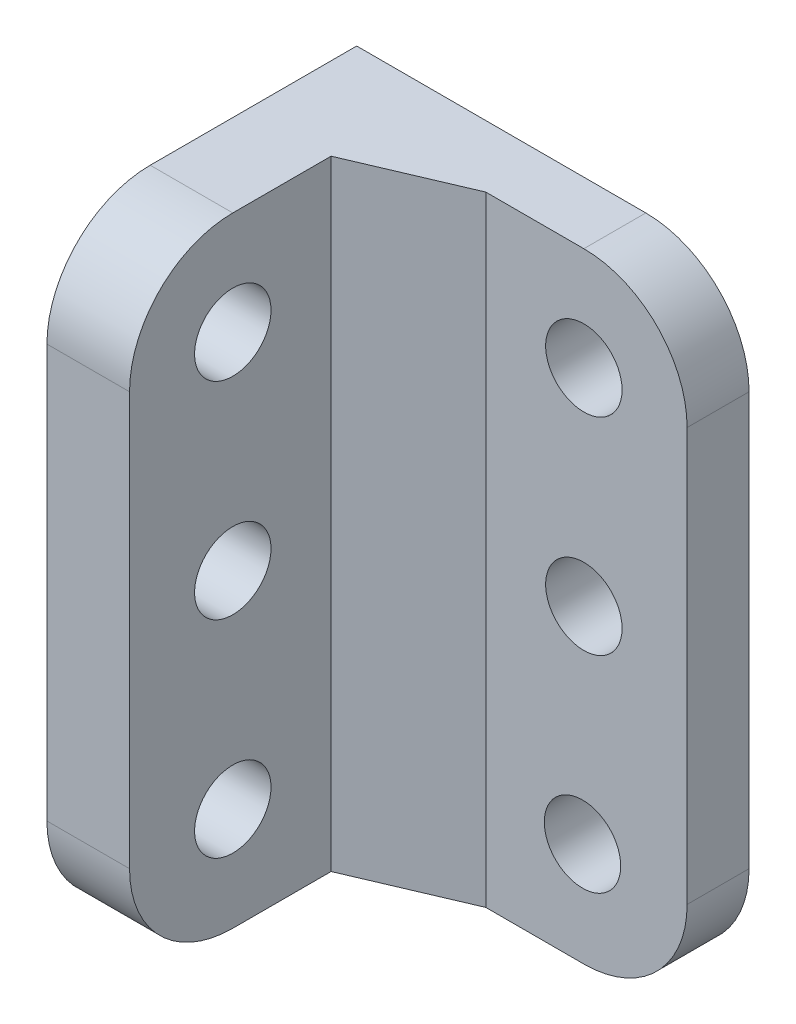
SolidWorks part; units mm, degrees
material "Copper"
ref_plane "Front Plane" through (0, 0, 0) normal (0, 0, 1) x (1, 0, 0)
ref_plane "Top Plane" through (0, 0, 0) normal (0, 1, 0) x (1, 0, 0)
ref_plane "Right Plane" through (0, 0, 0) normal (1, 0, 0) x (0, 0, -1)
sketch "Sketch1" plane through (0, 0, 0) normal (0, 1, 0) x (1, 0, 0)
  line L0 (0, 0) -> (24.13, 0)
  line L1 (24.13, 0) -> (24.13, -3.81)
  line L2 (24.13, -3.81) -> (11.7475, -3.81)
  line L3 (11.7475, -3.81) -> (5.08, -6.6548)
  line L4 (5.08, -6.6548) -> (5.08, -19.05)
  line L5 (5.08, -19.05) -> (0, -19.05)
  line L6 (0, -19.05) -> (0, 0)
  dimension "D1" = 24.13
  dimension "D2" = 19.05
  dimension "D3" = 12.3952
  dimension "D4" = 3.81
  dimension "D5" = 5.08
  dimension "D6" = 12.3825
extrude "Base Extrude" add sketch "Sketch1" along normal blind 38.1
sketch "Sketch2" plane through (0, 0, 3.81) normal (0, 0, 1) x (1, 0, 0)
  line L1 (0, 19.05) -> (24.13, 19.05) construction
  line L2 (0, 38.1) -> (0, 0) construction
  line L3 (24.13, 38.1) -> (24.13, 0) construction
  circle A0 centre (17.6973, 6.35) radius 2.3495
  circle A1 centre (17.78, 19.05) radius 2.3495
  circle A2 centre (17.78, 31.75) radius 2.3495
  dimension "D4" = 4.699
  dimension "D1" = 12.7
  dimension "D2" = 12.7
  dimension "D3" = 6.35
extrude "Motor Hole Cut" cut sketch "Sketch2" against normal through all
sketch "Sketch3" plane through (5.08, 0, 0) normal (1, 0, 0) x (0, 0, -1)
  line L0 (-19.05, 19.05) -> (0, 19.05) construction
  line L1 (-19.05, 38.1) -> (-19.05, 0) construction
  line L2 (0, 38.1) -> (0, 0) construction
  circle A0 centre (-12.7, 31.75) radius 2.3495
  circle A1 centre (-12.7, 19.05) radius 2.3495
  circle A2 centre (-12.7, 6.35) radius 2.3495
  dimension "D2" = 4.699
  dimension "D1" = 12.7
  dimension "D3" = 12.7
  dimension "D4" = 12.7
extrude "Mounting Hole Cut" cut sketch "Sketch3" against normal through all
fillet "Corner Fillets" radius 6.35 4 edges at (24.13, 38.1, 1.905) (24.13, 0, 1.905) (2.54, 0, 19.05) (2.54, 38.1, 19.05)
